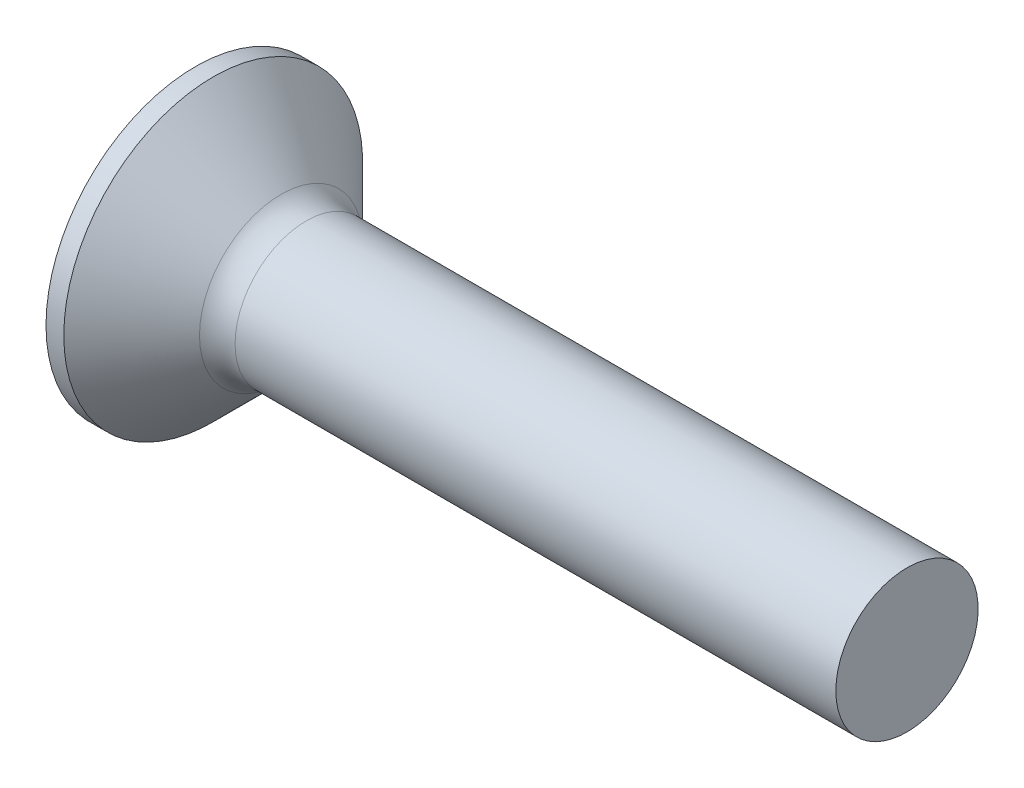
SolidWorks part; units mm, degrees
ref_plane "Plane1" through (0, 0, 0) normal (0, 0, 1) x (1, 0, 0)
ref_plane "Plane2" through (0, 0, 0) normal (0, 1, 0) x (1, 0, 0)
ref_plane "Plane3" through (0, 0, 0) normal (1, 0, 0) x (0, 0, -1)
sketch "BodySke" plane through (0, 0, 0) normal (0, 0, 1) x (1, 0, 0)
  line L0 (0, 0) -> (0, 4.2)
  line L1 (0, 4.2) -> (0.5, 4.2)
  line L2 (2.7, 2) -> (20, 2)
  line L3 (20, 2) -> (20, 0)
  line L4 (20, 0) -> (0, 0)
  line L5 (-6.35, 0) -> (82.55, 0) construction
  line L6 (2.7, -2) -> (20, -2) construction
  line L7 (0.5, -4.2) -> (2.7, -2) construction
  line L8 (0.5, 4.2) -> (2.7, 2)
  line L9 (0, -4.2) -> (0.5, -4.2) construction
  line L10 (3.4, 3.5875) -> (3.4, -5.9375) construction
  line L11 (0, 6.35) -> (0, -3.175) construction
  dimension "Diameter" = 4
  dimension "Length" = 20
  dimension "Head_ht" = 2.7
  dimension "Head_dia" = 8.4
  dimension "Head_ang" = 90
  dimension "D6" = 0.5
  dimension "Advance" = 0.7
  dimension "Thread_nom" = 20
revolve "Base-Revolve" add sketch "BodySke"
cosmetic thread "ThreadCosmetic"
fillet "Fillet1" radius 1 1 edges at (2.7, 0, 2)
sketch "Sketch3" plane through (0, 0, 0) normal (-1, 0, 0) x (0, 0, 1)
  line L0 (-0.515, 2.2) -> (0.515, 2.2)
  line L1 (0.515, 2.2) -> (0.515, -2.2)
  line L2 (0.515, -2.2) -> (-0.515, -2.2)
  line L3 (-0.515, -2.2) -> (-0.515, 2.2)
  dimension "D1" = 2.2
  dimension "Cross_dia" = 4.4
  dimension "D2" = 0.515
  dimension "Cross_width" = 1.03
ref_plane "Plane4" through (2.51, 0, 0) normal (-1, 0, 0) x (0, 0, 1)
sketch "Sketch4" plane through (2.51, 0, 0) normal (-1, 0, 0) x (0, 0, 1)
  line L0 (-0.515, 0.9486) -> (0.515, 0.9486)
  line L3 (0.515, 0.9486) -> (0.515, -0.9486)
  line L4 (0.515, -0.9486) -> (-0.515, -0.9486)
  line L5 (-0.515, -0.9486) -> (-0.515, 0.9486)
  dimension "D1" = 1.03
  dimension "D2" = 1.8971
  dimension "D3" = 0.515
  dimension "D4" = 0.9486
loft "Recess" cut profiles "Sketch3", "Sketch4"
pattern_circular "RecPat" count 2 every 90 about axis through (0, 0, 0) along (1, 0, 0) of "Recess"
sketch "RecCorSke" plane through (0, 0, 0) normal (0, 0, 1) x (1, 0, 0)
  line L0 (-3.175, 0) -> (15.875, 0) construction
  line L2 (0, 0) -> (0, 1.0265)
  line L3 (0, 1.0265) -> (2.51, 0.851)
  line L4 (2.51, 0.851) -> (2.7865, 0)
  line L5 (2.7865, 0) -> (0, 0)
  dimension "Diameter" = 1.702
  dimension "Depth" = 2.51
  dimension "Draft_angle" = 4
  dimension "Bottom_angle" = 18
revolve "RecessCore" cut sketch "RecCorSke" angle 360 about L0
sketch "ThdSchSke" plane through (0, 0, 0) normal (0, 0, 1) x (1, 0, 0)
  line L0 (3.4, -1.61) -> (3.1269, -2)
  line L1 (3.4, -1.61) -> (3.6731, -2)
  line L2 (3.6731, -2) -> (3.6731, -2.5)
  line L3 (-3.175, 0) -> (5.1513, 0) construction
  line L5 (3.6731, -2.5) -> (3.1269, -2.5)
  line L6 (3.1269, -2.5) -> (3.1269, -2)
  line L7 (0, 4.2) -> (0, -4.2) construction
  dimension "Thread_minor" = 3.22
  dimension "Diameter" = 4
  dimension "Start" = 3.4
  dimension "SideAngle" = 55
  dimension "VeeAngle" = 70
  dimension "Overcut" = 5
revolve "ThreadSchematic" [suppressed] cut sketch "ThdSchSke" angle 360 about L3
pattern_linear "ThdSchPat" [suppressed]
equation "\"D1@Sketch3\" = \"Cross_dia@Sketch3\" / 2"
equation "\"D2@Sketch3\" = \"Cross_width@Sketch3\" / 2"
equation "\"Depth@RecCorSke\" = \"Cross_depth@Plane4\""
equation "\"D1@Sketch4\" = \"Cross_width@Sketch3\""
equation "\"D2@Sketch4\" = \"Cross_dia@Sketch3\" - 2.0 * \"Cross_depth@Plane4\" * tan(26.5  * 0.017453292)"
equation "\"D3@Sketch4\" = \"D1@Sketch4\" / 2"
equation "\"D4@Sketch4\" = \"D2@Sketch4\" / 2"
equation "\"Thread_length@ThreadCosmetic\" = ((sgn( (\"Length@BodySke\" - \"Advance@BodySke\" * 1.0 - \"Head_ht@BodySke\" ) - \"Thread_nom@BodySke\" )-1)*( (\"Length@BodySke\" - \"Advance@BodySke\" * 1.0 - \"Head_ht@BodySke\" ) - \"Thread_nom@BodySke\" ))/-2+ \"Thread_nom@BodySke\""
equation "\"Thread_minor@ThdSchSke\" = \"Thread_minor@ThreadCosmetic\""
equation "\"Diameter@ThdSchSke\" = \"Diameter@BodySke\""
equation "\"Overcut@ThdSchSke\" = \"Diameter@BodySke\" * 1.25"
equation "\"Start@ThdSchSke\" = 0.000001 + \"Length@BodySke\" - \"Thread_length@ThreadCosmetic\"  '---Countersunk---"
equation "\"Num_threads@ThdSchPat\" = int( \"Thread_length@ThreadCosmetic\" / \"Advance@BodySke\" + 0.999 )  + 1"
equation "\"Advance@ThdSchPat\" = \"Thread_length@ThreadCosmetic\" /  (\"Num_threads@ThdSchPat\" - 1) 'relax it"
